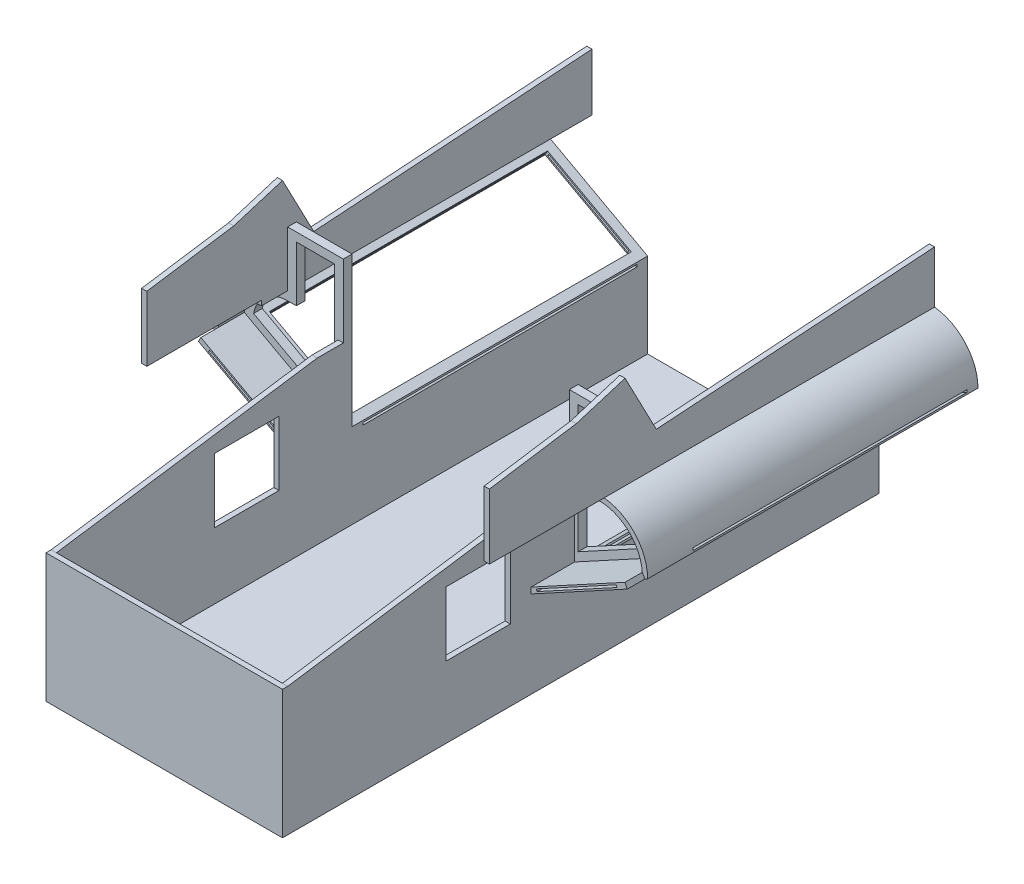
SolidWorks part; units mm, degrees
material "Balsa"
ref_plane "Front Plane" through (0, 0, 0) normal (0, 0, 1) x (1, 0, 0)
ref_plane "Top Plane" through (0, 0, 0) normal (0, 1, 0) x (1, 0, 0)
ref_plane "Right Plane" through (0, 0, 0) normal (1, 0, 0) x (0, 0, -1)
sketch "Sketch1" plane through (0, 0, 0) normal (0, 0, 1) x (1, 0, 0)
  line L0 (-625, 133.7223) -> (-340, -21.2777)
  line L1 (-340, -271.2777) -> (340, -271.2777)
  line L2 (-340, -271.2777) -> (-340, -21.2777)
  line L4 (-500, 272.9164) -> (-500, 422.9164)
  line L5 (0, 497.2476) -> (0, -497.2476) construction
  line L9 (-485, 407.9164) -> (-485, 258.7223)
  line L11 (-609.6934, 142.4725) -> (-325, -12.3607)
  line L12 (-325, -12.3607) -> (-325, -256.2777)
  line L13 (-325, -256.2777) -> (325, -256.2777)
  line L14 (325, -12.3607) -> (325, -256.2777)
  line L15 (609.6934, 142.4725) -> (325, -12.3607)
  line L16 (485, 407.9164) -> (485, 258.7223)
  line L17 (500, 272.9164) -> (500, 422.9164)
  line L18 (340, -271.2777) -> (340, -21.2777)
  line L19 (625, 133.7223) -> (340, -21.2777)
  line L20 (500, 422.9164) -> (485, 422.9164)
  line L21 (485, 422.9164) -> (485, 407.9164)
  line L22 (-500, 422.9164) -> (-485, 422.9164)
  line L23 (-485, 422.9164) -> (-485, 407.9164)
  arc A0 (-500, 272.9164) -> (-625, 133.7223) centre (-485, 133.7223) ccw
  arc A2 (-485, 258.7223) -> (-609.6934, 142.4725) centre (-485, 133.7223) ccw
  arc A3 (485, 258.7223) -> (609.6934, 142.4725) centre (485, 133.7223) cw
  arc A4 (500, 272.9164) -> (625, 133.7223) centre (485, 133.7223) cw
  point P1 (0, 0)
  point P7 (-500, 272.9164)
  point P30 (500, 272.9164)
  dimension "D5" = 280
  dimension "D10" = 15
  dimension "D11" = 15
  dimension "D1" = 680
  dimension "D2" = 250
  dimension "D3" = 405
  dimension "D4" = 285
  dimension "D6" = 125
  dimension "D7" = 150
  dimension "D8" = 15
  dimension "D13" = 15
extrude "Boss-Extrude1" add sketch "Sketch1" along normal blind 950
sketch "Sketch2" plane through (500, 0, 0) normal (1, 0, 0) x (0, 0, -1)
  line L0 (-950, 358.7223) -> (0, 422.9164)
  line L1 (-950, 272.9164) -> (-950, 422.9164) construction
  line L2 (-950, 422.9164) -> (0, 422.9164) construction
  line L3 (-950, -271.2777) -> (0, -271.2777) construction
  line L4 (-950, 358.7223) -> (-950, 422.9164)
  line L5 (-950, 422.9164) -> (0, 422.9164)
  dimension "D1" = 630
extrude "Cut-Extrude1" cut sketch "Sketch2" against normal up to surface (1000 mm away) up to face at (-500, 347.9164, 475)
sketch "Sketch3" plane through (-500, 0, 0) normal (-1, 0, 0) x (0, 0, 1)
  line L0 (800, 368.8582) -> (890, 540.8582)
  line L1 (890, 540.8582) -> (1030, 497.8582)
  line L2 (1030, 497.8582) -> (1280, 459.8582)
  line L3 (1280, 459.8582) -> (1280, 272.9164)
  line L4 (800, 368.8582) -> (800, 272.9164)
  line L5 (800, 272.9164) -> (1280, 272.9164)
  line L6 (0, 422.9164) -> (0, 272.9164) construction
  line L7 (0, 422.9164) -> (950, 358.7223) construction
  dimension "D1" = 90
  dimension "D2" = 172
  dimension "D3" = 140
  dimension "D4" = 43
  dimension "D5" = 250
  dimension "D6" = 38
  dimension "D7" = 800
  dimension "D8" = 0
extrude "Boss-Extrude2" add sketch "Sketch3" against normal up to surface (1000 mm away) up to face at (500, 331.8679, 475)
sketch "Sketch4" plane through (0, 0, 1280) normal (0, 0, 1) x (1, 0, 0)
  line L0 (-485, 272.9164) -> (-485, 540.8582)
  line L1 (500, 540.8582) -> (-500, 540.8582) construction
  line L2 (485, 272.9164) -> (485, 540.8582)
  line L3 (485, 540.8582) -> (-485, 540.8582)
  line L4 (-485, 272.9164) -> (485, 272.9164)
extrude "Cut-Extrude2" cut sketch "Sketch4" against normal up to surface (480 mm away) up to face at (0, 320.8873, 800)
sketch "Sketch9" plane through (0, 0, 950) normal (0, 0, 1) x (1, 0, 0)
  line L0 (-609.6934, 142.4725) -> (-616.8599, 129.2952)
  line L5 (-625, 133.7223) -> (-340, -21.2777) construction
  line L6 (-616.8599, 129.2952) -> (-340, -21.2777)
  line L7 (-340, -21.2777) -> (-332.8334, -8.1005)
  line L8 (-332.8334, -8.1005) -> (-609.6934, 142.4725)
extrude "Boss-Extrude4" add sketch "Sketch9" along normal blind 50
sketch "Sketch14" plane through (-485, 0, 0) normal (1, 0, 0) x (0, 0, -1)
  line L0 (-875, 396.8995) -> (-875, 258.7223)
  line L2 (-950, 258.7223) -> (0, 258.7223) construction
  line L3 (-875, 258.7223) -> (-850, 258.7223)
  line L4 (-850, 258.7223) -> (-850, 396.8995)
  line L5 (-850, 396.8995) -> (-875, 396.8995)
  dimension "D1" = 25
  dimension "D2" = 25
  dimension "D3" = 90
  dimension "D4" = 850
  dimension "D5" = 405
extrude "Boss-Extrude9" add sketch "Sketch14" along normal blind 25
sketch "Sketch15" plane through (0, 0, 875) normal (0, 0, 1) x (1, 0, 0)
  line L0 (-460, 258.7223) -> (-460, 233.7223)
  line L1 (-609.6934, 142.4725) -> (-587.7313, 130.5282)
  line L2 (-332.8334, -8.1005) -> (-609.6934, 142.4725) construction
  line L3 (-460, 258.7223) -> (-485, 258.7223) construction
  line L4 (-485, 258.7223) -> (-460, 258.7223)
  line L5 (-485, 233.7223) -> (-460, 233.7223)
  line L6 (-587.7313, 130.5282) -> (-584.9827, 135.582)
  arc A0 (-485, 258.7223) -> (-609.6934, 142.4725) centre (-485, 133.7223) ccw
  arc A1 (-485, 258.7223) -> (-609.6934, 142.4725) centre (-485, 133.7223) ccw construction
  arc A2 (-485, 233.7223) -> (-584.9827, 135.582) centre (-485, 133.7223) ccw
  dimension "D1" = 0
  dimension "D2" = 250
  dimension "D3" = 200
  dimension "D4" = 360
  dimension "D5" = 0
  dimension "D6" = 25
extrude "Boss-Extrude10" add sketch "Sketch15" against normal blind 25
sketch "Sketch16" plane through (0, 0, 875) normal (0, 0, 1) x (1, 0, 0)
  line L0 (-587.7313, 130.5282) -> (-325, -12.3607)
  line L1 (-325, -12.3607) -> (-325, 12.6393)
  line L2 (-325, 12.6393) -> (-583.1202, 153.0204)
  line L3 (-583.1202, 153.0204) -> (-587.7313, 130.5282)
  arc A0 (-485, 233.7223) -> (-584.9827, 135.582) centre (-485, 133.7223) ccw construction
  dimension "D1" = 25
extrude "Boss-Extrude11" add sketch "Sketch16" against normal blind 25
sketch "Sketch17" plane through (0, 0, 875) normal (0, 0, 1) x (1, 0, 0)
  line L0 (-325, 12.6393) -> (-325, 392.6393)
  line L1 (-325, 392.6393) -> (-350, 392.6393)
  line L2 (-350, 392.6393) -> (-350, 26.2358)
  line L3 (-325, 12.6393) -> (-583.1202, 153.0204) construction
  line L4 (-350, 26.2358) -> (-325, 12.6393)
  dimension "D1" = 25
  dimension "D2" = 380
extrude "Boss-Extrude12" add sketch "Sketch17" against normal blind 25
sketch "Sketch18" plane through (0, 0, 875) normal (0, 0, 1) x (1, 0, 0)
  line L0 (-485, 459.8582) -> (-485, 272.9164) construction
  line L1 (-325, 392.6393) -> (-485, 392.6393)
  line L2 (-325, 392.6393) -> (-325, 417.6393)
  line L3 (-325, 417.6393) -> (-485, 417.6393)
  line L4 (-485, 392.6393) -> (-485, 417.6393)
  dimension "D1" = 25
extrude "Boss-Extrude13" add sketch "Sketch18" against normal blind 25
sketch "Sketch19" plane through (-79.3744, -145.9466, 0) normal (0.4778, 0.8785, 0) x (0.8785, -0.4778, 0)
  line L0 (-279.6017, 0) -> (-603.6752, 0) construction
  line L1 (-578.6752, -25) -> (-304.6017, -25)
  line L2 (-578.6752, -25) -> (-578.6752, -825)
  line L3 (-578.6752, -825) -> (-304.6017, -825)
  line L4 (-304.6017, -25) -> (-304.6017, -825)
  line L5 (-279.6017, -850) -> (-279.6017, 0) construction
  line L6 (-603.6752, -850) -> (-603.6752, 0) construction
  line L7 (-603.6752, -850) -> (-279.6017, -850) construction
  dimension "D1" = 25
  dimension "D2" = 25
  dimension "D3" = 25
  dimension "D4" = 25
extrude "Cut-Extrude3" cut sketch "Sketch19" against normal blind 25
sketch "Sketch21" plane through (0, 0, 825) normal (0, 0, -1) x (-1, 0, 0)
  line L0 (584.6103, 123.7084) -> (354.383, -1.503)
  line L1 (354.383, -1.503) -> (357.2496, -6.7739)
  line L2 (357.2496, -6.7739) -> (587.477, 118.4375)
  line L3 (587.477, 118.4375) -> (584.6103, 123.7084)
  line L5 (594.8978, 117.3509) -> (587.7313, 130.5282) construction
  line L7 (587.7313, 130.5282) -> (346.9621, -0.4164) construction
  line L11 (354.1287, -13.5937) -> (346.9621, -0.4164) construction
  dimension "D1" = 6
  dimension "D2" = 90
  dimension "D3" = 6
  dimension "D4" = 4.5
  dimension "D6" = 6
extrude "Cut-Extrude4" cut sketch "Sketch21" against normal through all both and the other way through all
sketch "Sketch22" plane through (-508.3568, 276.4748, 0) normal (0.8785, -0.4778, 0) x (0, 0, -1)
  line L0 (-25, -181.1346) -> (-25, -166.1346) construction
  line L1 (-819, -170.6346) -> (-31, -170.6346)
  line L2 (-819, -170.6346) -> (-819, -176.6346)
  line L3 (-819, -176.6346) -> (-31, -176.6346)
  line L4 (-31, -170.6346) -> (-31, -176.6346)
  line L5 (-25, -181.1346) -> (-825, -181.1346) construction
  line L6 (-825, -181.1346) -> (-825, -166.1346) construction
  dimension "D1" = 6
  dimension "D2" = 4.5
  dimension "D3" = 6
  dimension "D4" = 6
extrude "Cut-Extrude5" cut sketch "Sketch22" along normal blind 350 from offset 45
ref_plane "Symetric Plan 1" through (0, 0, 0) normal (1, 0, 0) x (0, 0, -1)
mirror "Mirror1" about plane through (0, 0, 0) normal (1, 0, 0) of "Cut-Extrude5", "Cut-Extrude4", "Cut-Extrude3", "Boss-Extrude4", "Boss-Extrude10", "Boss-Extrude11", "Boss-Extrude12", "Boss-Extrude13", "Boss-Extrude9"
sketch "Sketch23" plane through (-340, 0, 0) normal (-1, 0, 0) x (0, 0, 1)
  line L0 (0, -21.2777) -> (0, -271.2777) construction
  line L1 (950, -271.2777) -> (1700, -271.2777)
  line L2 (950, -271.2777) -> (950, -21.2777)
  line L3 (950, 208.7223) -> (1700, 98.7223)
  line L4 (1700, -271.2777) -> (1700, 98.7223)
  line L5 (950, -21.2777) -> (873.5, -21.2777)
  line L6 (873.5, -21.2777) -> (873.5, 208.7223)
  line L7 (873.5, 208.7223) -> (950, 208.7223)
  dimension "D1" = 1700
  dimension "D2" = 370
  dimension "D3" = 480
  dimension "D4" = 76.5
  dimension "D5" = 250
extrude "Boss-Extrude14" add sketch "Sketch23" against normal blind 15
mirror "Mirror2" about plane through (0, 0, 0) normal (1, 0, 0) of "Boss-Extrude14"
sketch "Sketch24" plane through (0, -256.2777, 0) normal (0, 1, 0) x (1, 0, 0)
  line L1 (-325, -950) -> (325, -950)
  line L2 (-325, -950) -> (-325, -1700)
  line L3 (-325, -1700) -> (325, -1700)
  line L4 (325, -950) -> (325, -1700)
  dimension "D1" = 750
  dimension "D2" = 650
extrude "Boss-Extrude15" add sketch "Sketch24" against normal blind 15
sketch "Sketch25" plane through (0, 0, 1700) normal (0, 0, 1) x (1, 0, 0)
  line L1 (-340, -271.2777) -> (340, -271.2777)
  line L2 (-340, -271.2777) -> (-340, 98.7223)
  line L3 (-340, 98.7223) -> (340, 98.7223)
  line L4 (340, -271.2777) -> (340, 98.7223)
extrude "Boss-Extrude16" add sketch "Sketch25" along normal blind 15
sketch "Sketch26" plane through (340, 0, 0) normal (1, 0, 0) x (0, 0, -1)
  line L0 (-1715, -271.2777) -> (-1715, 98.7223) construction
  line L1 (-1245, 118.7223) -> (-1060, 118.7223)
  line L2 (-1245, 118.7223) -> (-1245, -66.2777)
  line L3 (-1245, -66.2777) -> (-1060, -66.2777)
  line L4 (-1060, 118.7223) -> (-1060, -66.2777)
  line L5 (-1715, -271.2777) -> (0, -271.2777) construction
  dimension "D1" = 470
  dimension "D2" = 205
  dimension "D3" = 185
  dimension "D4" = 185
extrude "Cut-Extrude6" cut sketch "Sketch26" against normal up to surface (680 mm away) up to face at (-340, 2.1373, 983)
